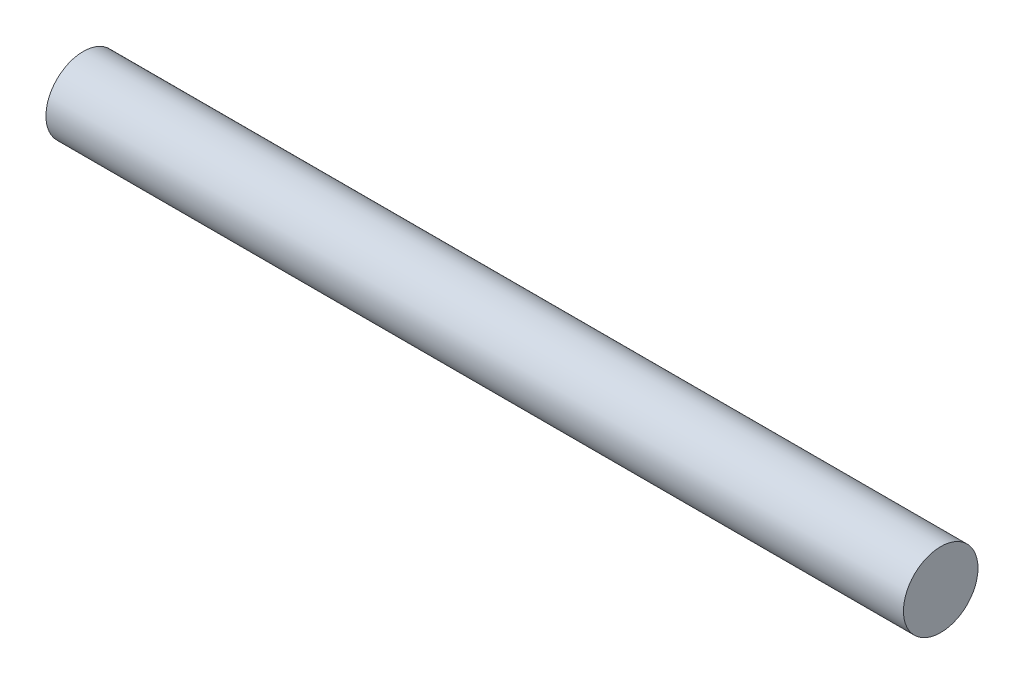
SolidWorks part; units mm, degrees
material "Stainless Steel (ferritic)"
ref_plane "Front Plane" through (0, 0, 0) normal (0, 0, 1) x (1, 0, 0)
ref_plane "Top Plane" through (0, 0, 0) normal (0, 1, 0) x (1, 0, 0)
ref_plane "Right Plane" through (0, 0, 0) normal (1, 0, 0) x (0, 0, -1)
sketch "Sketch2" plane through (0, 0, 0) normal (1, 0, 0) x (0, 0, -1)
  circle A0 centre (0, 0) radius 1.5
  dimension "D1" = 3
extrude "Boss-Extrude1" add sketch "Sketch2" along normal blind 34.5
